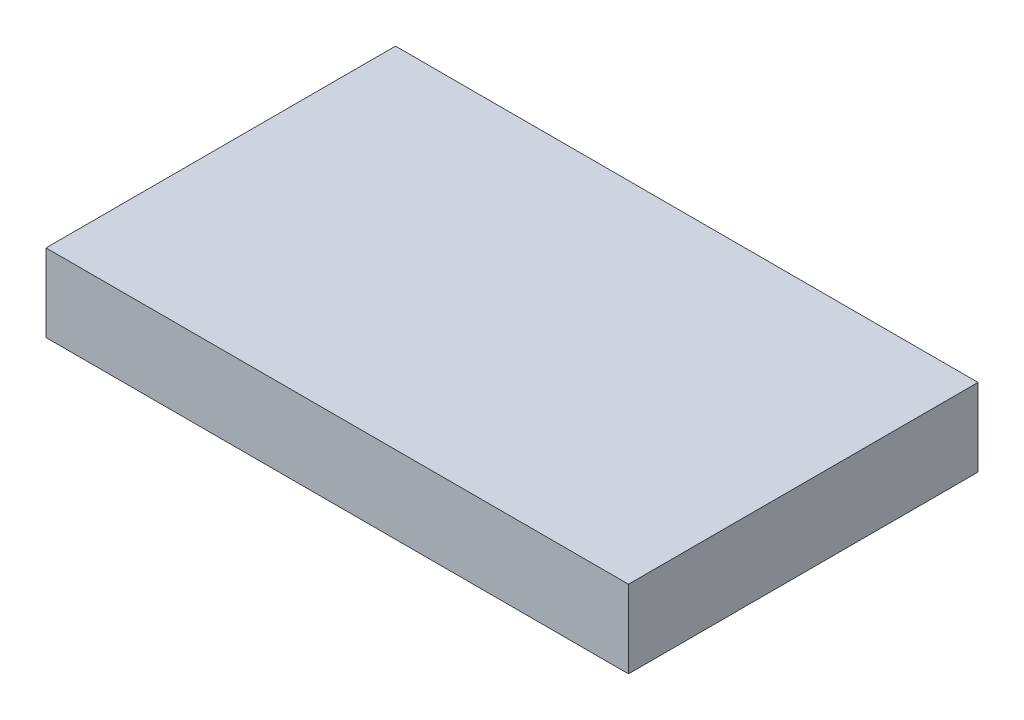
SolidWorks part; units mm, degrees
ref_plane "Alzado" through (0, 0, 0) normal (0, 0, 1) x (1, 0, 0)
ref_plane "Planta" through (0, 0, 0) normal (0, 1, 0) x (1, 0, 0)
ref_plane "Vista lateral" through (0, 0, 0) normal (1, 0, 0) x (0, 0, -1)
sketch "Croquis1" plane through (0, 0, 0) normal (0, 0, 1) x (1, 0, 0)
  line L0 (-82.0547, 15.0825) -> (-82.0547, -4.9175)
  line L1 (-82.0547, -4.9175) -> (67.9453, -4.9175)
  line L2 (67.9453, -4.9175) -> (67.9453, 15.0825)
  line L3 (67.9453, 15.0825) -> (-82.0547, 15.0825)
  dimension "D1" = 20
  dimension "D2" = 150
extrude "Saliente-Extruir2" add sketch "Croquis1" along normal blind 90
